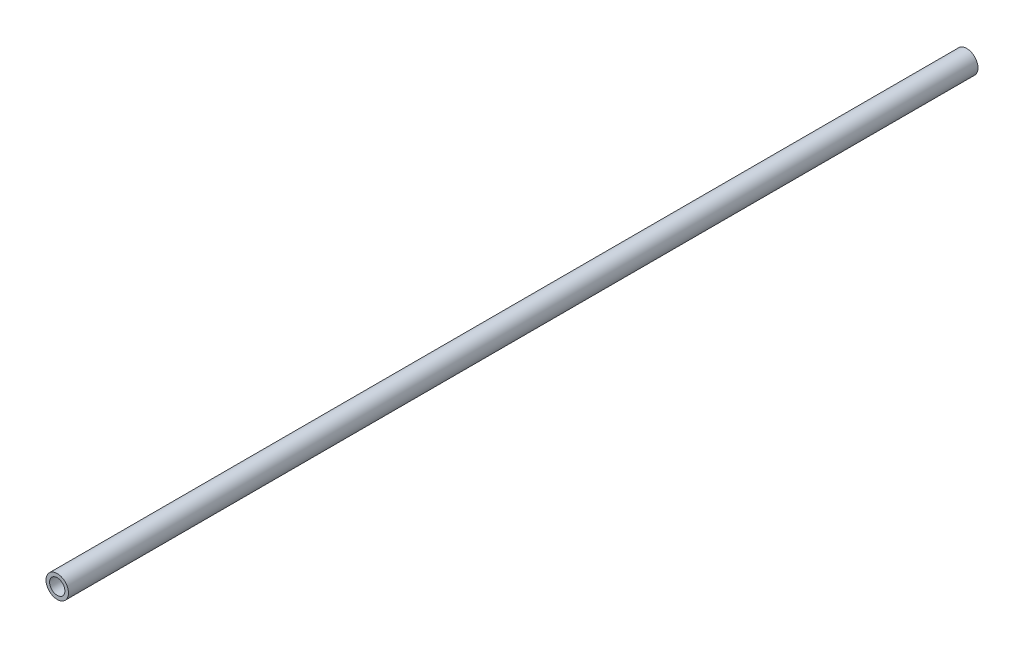
SolidWorks part; units mm, degrees
ref_plane "Piano frontale" through (0, 0, 0) normal (0, 0, 1) x (1, 0, 0)
ref_plane "Piano superiore" through (0, 0, 0) normal (0, 1, 0) x (1, 0, 0)
ref_plane "Piano destro" through (0, 0, 0) normal (1, 0, 0) x (0, 0, -1)
sketch "Schizzo1" plane through (0, 0, 0) normal (0, 0, 1) x (1, 0, 0)
  circle A0 centre (0, 0) radius 2.5
  dimension "D1" = 5
extrude "Estrusione-Estrusione1" add sketch "Schizzo1" against normal blind 202
hole_wizard "Foro per Vite M3-1" positions "Schizzo3" profile "Schizzo5" hole size "M3" standard "AS"
sketch "Schizzo3" plane through (0, 0, 0) normal (0, 0, 1) x (1, 0, 0)
  point P0 (0, 0)
sketch "Schizzo5" plane through (0, 0, 0) normal (1, 0, 0) x (0, -1, 0)
  line L0 (0, 0) -> (0, 11)
  line L1 (0, 11) -> (1.7, 9.9785)
  line L2 (1.7, 9.9785) -> (1.7, 0)
  line L5 (1.7, 0) -> (0, 0)
  line L10 (0, 11) -> (-1.7, 9.9785) construction
  line L11 (0, -6.35) -> (0, 107.95) construction
  dimension "Hole Dia." = 3.4
  dimension "Hole Depth" = 11
  dimension "Drill Angle" = 118
hole_wizard "Foro per Vite M3-2" positions "Schizzo6" profile "Schizzo7" hole size "M3" standard "AS"
sketch "Schizzo6" plane through (0, 0, -202) normal (0, 0, -1) x (-1, 0, 0)
  point P0 (0, 0)
sketch "Schizzo7" plane through (0, 0, -202) normal (1, 0, 0) x (0, 1, 0)
  line L0 (0, 0) -> (0, 11)
  line L1 (0, 11) -> (1.7, 9.9785)
  line L2 (1.7, 9.9785) -> (1.7, 0)
  line L5 (1.7, 0) -> (0, 0)
  line L10 (0, 11) -> (-1.7, 9.9785) construction
  line L11 (0, -6.35) -> (0, 107.95) construction
  dimension "Hole Dia." = 3.4
  dimension "Hole Depth" = 11
  dimension "Drill Angle" = 118
